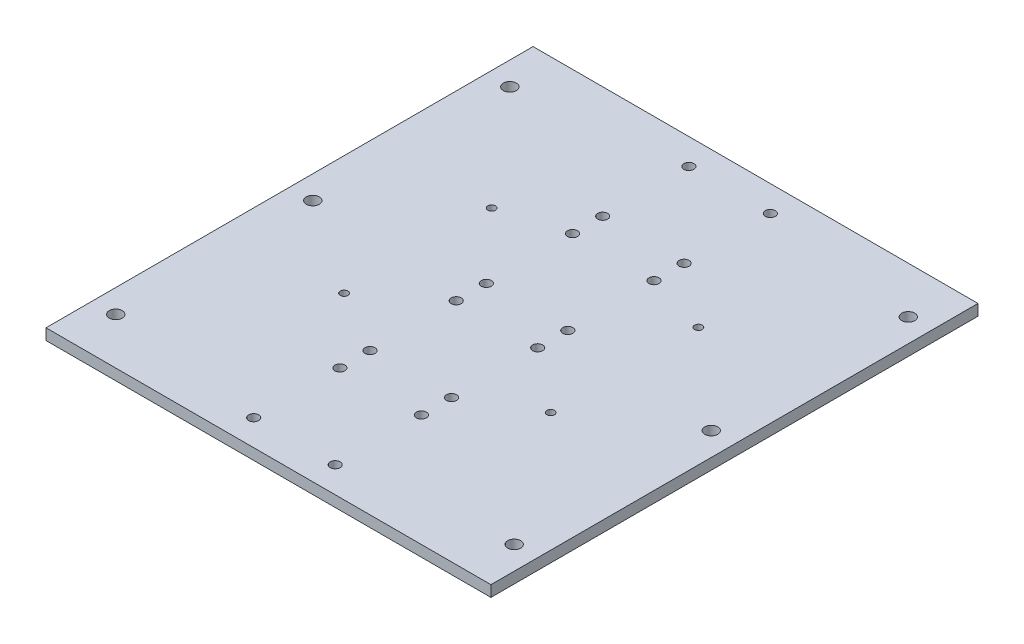
SolidWorks part; units mm, degrees
material "Acrylic (Medium-high impact)"
ref_plane "Front Plane" through (0, 0, 0) normal (0, 0, 1) x (1, 0, 0)
ref_plane "Top Plane" through (0, 0, 0) normal (0, 1, 0) x (1, 0, 0)
ref_plane "Right Plane" through (0, 0, 0) normal (1, 0, 0) x (0, 0, -1)
sketch "Sketch1" plane through (0, 0, 0) normal (0, 1, 0) x (1, 0, 0)
  line L0 (6.6616, -70.0394) -> (6.6616, -81.2029) construction
  line L2 (-71.5124, 128.3221) -> (119.8876, 128.3221)
  line L3 (-71.5124, 128.3221) -> (-71.5124, -81.2029)
  line L4 (-71.5124, -81.2029) -> (119.8876, -81.2029)
  line L5 (119.8876, 128.3221) -> (119.8876, -81.2029)
  line L13 (24.1876, 128.3221) -> (24.1876, -81.2029) construction
  line L14 (6.6616, 117.1586) -> (41.7136, 117.1586) construction
  line L15 (6.6616, 117.1586) -> (6.6616, 80.0746) construction
  line L16 (-20.2624, 59.2721) -> (68.6376, 59.2721) construction
  line L17 (-20.2624, 59.2721) -> (-20.2624, -4.2279) construction
  line L18 (-20.2624, -4.2279) -> (68.6376, -4.2279) construction
  line L19 (68.6376, 59.2721) -> (68.6376, -4.2279) construction
  line L20 (6.6616, 80.0746) -> (41.7136, 80.0746) construction
  line L21 (41.7136, 117.1586) -> (41.7136, 80.0746) construction
  line L22 (6.6616, 67.1206) -> (41.7136, 67.1206) construction
  line L23 (6.6616, 67.1206) -> (6.6616, 30.0366) construction
  line L24 (6.6616, 30.0366) -> (41.7136, 30.0366) construction
  line L25 (41.7136, 67.1206) -> (41.7136, 30.0366) construction
  line L26 (6.6616, 17.0826) -> (41.7136, 17.0826) construction
  line L27 (6.6616, 17.0826) -> (6.6616, -20.0014) construction
  line L28 (6.6616, -20.0014) -> (41.7136, -20.0014) construction
  line L29 (41.7136, 17.0826) -> (41.7136, -20.0014) construction
  line L30 (6.6616, -32.9554) -> (41.7136, -32.9554) construction
  line L31 (6.6616, -32.9554) -> (6.6616, -70.0394) construction
  line L32 (6.6616, -70.0394) -> (41.7136, -70.0394) construction
  line L33 (41.7136, -32.9554) -> (41.7136, -70.0394) construction
  line L34 (6.6616, 117.1586) -> (6.6616, 128.3221) construction
  circle A16 centre (-61.5124, 108.3221) radius 2.8
  circle A17 centre (-61.5124, 23.5721) radius 2.8
  circle A18 centre (-61.5124, -61.2029) radius 2.8
  circle A19 centre (109.8876, -61.2029) radius 2.8
  circle A20 centre (109.8876, 23.5721) radius 2.8
  circle A21 centre (109.8876, 108.3221) radius 2.8
  circle A22 centre (-20.2624, 59.2721) radius 1.65
  circle A23 centre (68.6376, 59.2721) radius 1.65
  circle A24 centre (-20.2624, -4.2279) radius 1.65
  circle A25 centre (68.6376, -4.2279) radius 1.65
  circle A26 centre (6.6616, -32.9554) radius 2.159
  circle A27 centre (41.7136, -32.9554) radius 2.159
  circle A28 centre (6.6616, -70.0394) radius 2.159
  circle A29 centre (41.7136, -70.0394) radius 2.159
  circle A30 centre (6.6616, 17.0826) radius 2.159
  circle A31 centre (41.7136, 17.0826) radius 2.159
  circle A32 centre (6.6616, -20.0014) radius 2.159
  circle A33 centre (41.7136, -20.0014) radius 2.159
  circle A34 centre (6.6616, 67.1206) radius 2.159
  circle A35 centre (41.7136, 67.1206) radius 2.159
  circle A36 centre (6.6616, 30.0366) radius 2.159
  circle A37 centre (41.7136, 30.0366) radius 2.159
  circle A38 centre (6.6616, 117.1586) radius 2.159
  circle A39 centre (41.7136, 117.1586) radius 2.159
  circle A40 centre (6.6616, 80.0746) radius 2.159
  circle A41 centre (41.7136, 80.0746) radius 2.159
  point P2 (24.1876, -70.0394)
  point P62 (24.1876, 59.2721)
  dimension "D1" = 4.318
  dimension "D2" = 4.318
  dimension "D16" = 4.318
  dimension "D17" = 4.318
  dimension "D18" = 4.318
  dimension "D19" = 4.318
  dimension "D20" = 4.318
  dimension "D21" = 12.954
  dimension "D29" = 37.084
  dimension "D30" = 35.052
  dimension "D31" = 37.084
  dimension "D32" = 69.05
  dimension "D38" = 5.6
  dimension "D39" = 5.6
  dimension "D40" = 5.6
  dimension "D41" = 5.6
  dimension "D42" = 5.6
  dimension "D43" = 5.6
  dimension "D57" = 3.3
  dimension "D58" = 3.3
  dimension "D59" = 3.3
  dimension "D60" = 3.3
  dimension "D7" = 4.318
  dimension "D8" = 4.318
  dimension "D9" = 4.318
  dimension "D10" = 4.318
  dimension "D11" = 4.318
  dimension "D12" = 4.318
  dimension "D13" = 4.318
  dimension "D14" = 4.318
  dimension "D15" = 4.318
  dimension "D22" = 12.954
  dimension "D23" = 12.954
  dimension "D24" = 35.052
  dimension "D25" = 37.084
  dimension "D26" = 35.052
  dimension "D27" = 37.084
  dimension "D28" = 35.052
  dimension "D35" = 191.4
  dimension "D36" = 209.525
  dimension "D44" = 10
  dimension "D45" = 20
  dimension "D46" = 10
  dimension "D47" = 104.75
  dimension "D48" = 20
  dimension "D49" = 10
  dimension "D50" = 10
  dimension "D51" = 20
  dimension "D52" = 10
  dimension "D53" = 104.75
  dimension "D54" = 10
  dimension "D55" = 20
  dimension "D61" = 63.5
  dimension "D63" = 88.9
extrude "Boss-Extrude1" add sketch "Sketch1" along normal blind 4.7625
